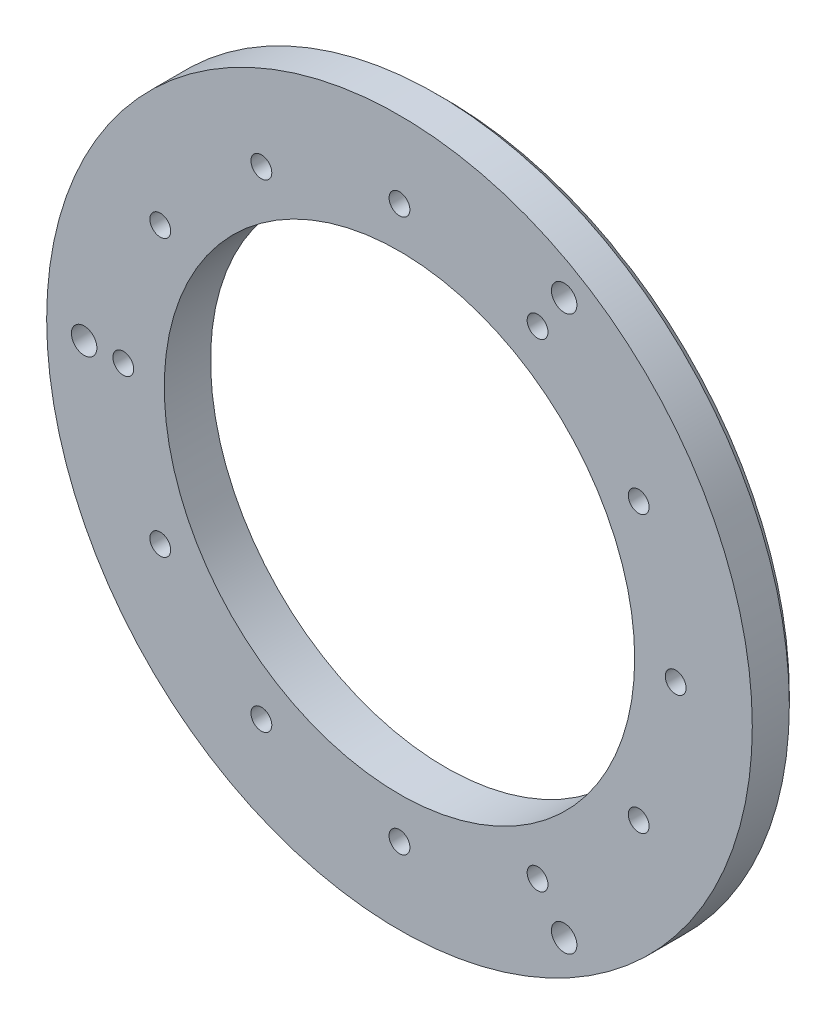
SolidWorks part; units mm, degrees
material "6061-T6 (SS)"
ref_plane "Plan de face" through (0, 0, 0) normal (0, 0, 1) x (1, 0, 0)
ref_plane "Plan de dessus" through (0, 0, 0) normal (0, 1, 0) x (1, 0, 0)
ref_plane "Plan de droite" through (0, 0, 0) normal (1, 0, 0) x (0, 0, -1)
sketch "Esquisse2" plane through (0, 0, 0) normal (0, 0, 1) x (1, 0, 0)
  circle A0 centre (0, 0) radius 76.2
  circle A1 centre (0, 0) radius 50.8
  dimension "D1" = 101.6
  dimension "D2" = 152.4
extrude "Boss.-Extru.1" add sketch "Esquisse2" along normal blind 10
chamfer "Chanfrein1" distance 2 angle 45 1 edges at (76.2, 0, 0)
hole_wizard "Dégagement #81" positions "Esquisse3" profile "Esquisse4" hole size "#8" standard "Ansi Inch" end condition through all
sketch "Esquisse3" plane through (0, 0, 0) normal (0, 0, -1) x (-1, 0, 0)
  point P0 (0, 59.65)
  point P3 (51.6584, 29.825)
  point P6 (29.825, 51.6584)
  point P9 (59.65, 0)
  point P12 (51.6584, -29.825)
  point P15 (29.825, -51.6584)
  point P18 (0, -59.65)
  point P21 (-29.825, -51.6584)
  point P24 (-51.6584, -29.825)
  point P27 (-59.65, 0)
  point P30 (-51.6584, 29.825)
  point P33 (-29.825, 51.6584)
sketch "Esquisse4" plane through (0, 59.65, 0) normal (1, 0, 0) x (0, 1, 0)
  line L0 (0, 0) -> (0, 10)
  line L1 (0, 10) -> (2.2479, 10)
  line L2 (2.2479, 10) -> (2.2479, 0)
  line L5 (2.2479, 0) -> (0, 0)
  line L11 (0, -6.35) -> (0, 107.95) construction
  dimension "Diamètre du perçage jusqu'au prochain" = 4.4958
  dimension "Profondeur du perçage jusqu'au prochain" = 10
hole_wizard "Fraisage pour vis à tête fraisée M51" positions "Esquisse7" profile "Esquisse8" countersink size "M5" standard "DIN" end condition through all
sketch "Esquisse7" plane through (0, 0, 0) normal (0, 0, -1) x (-1, 0, 0)
  circle A0 centre (0, 0) radius 68.1 construction
  point P0 (68.1, 0)
  point P2 (-35.565, -59.851)
  point P4 (-35.565, 59.851)
  dimension "D1" = 136.2
  dimension "D2" = 60
sketch "Esquisse8" plane through (-68.1, 0, 0) normal (1, 0, 0) x (0, 1, 0)
  line L0 (0, 0) -> (0, 10)
  line L1 (0, 10) -> (2.75, 10)
  line L2 (2.75, 10) -> (2.75, 2.45)
  line L3 (2.75, 2.45) -> (5.2, 0)
  line L5 (5.2, 0) -> (0, 0)
  line L6 (-2.75, 2.45) -> (-5.2, 0) construction
  line L11 (0, -6.35) -> (0, 107.95) construction
  dimension "Diamètre du perçage jusqu'au prochain" = 5.5
  dimension "Profondeur du perçage jusqu'au prochain" = 10
  dimension "Diamètre du fraisage entrant" = 10.4
  dimension "Angle du fraisage entrant" = 90
